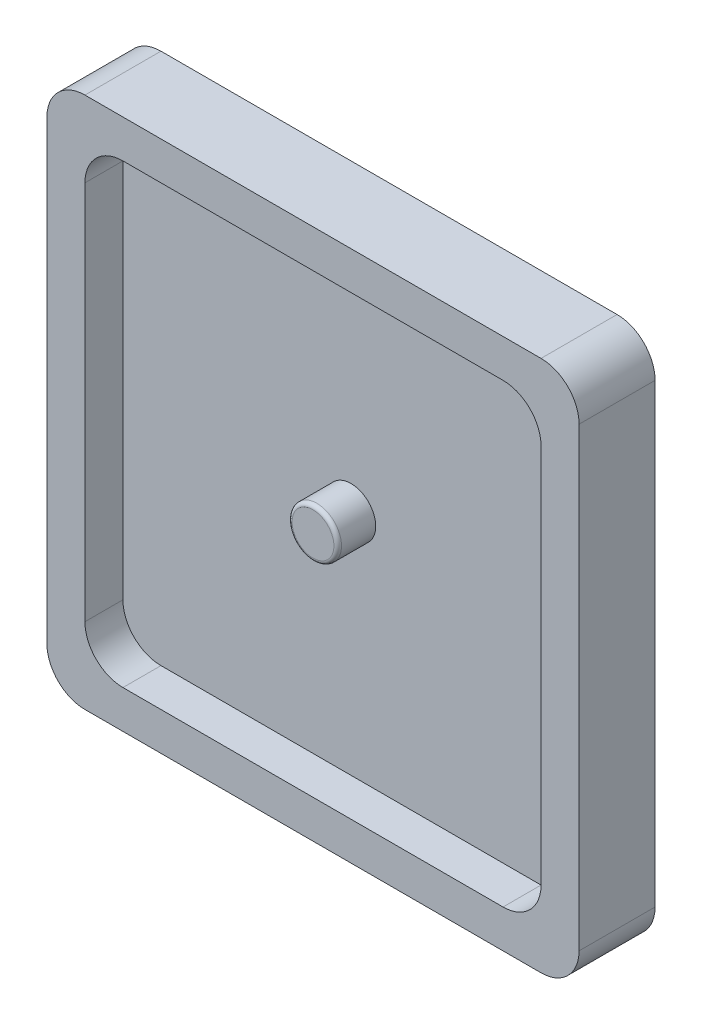
SolidWorks part; units mm, degrees
ref_plane "Plan de face" through (0, 0, 0) normal (0, 0, 1) x (1, 0, 0)
ref_plane "Plan de dessus" through (0, 0, 0) normal (0, 1, 0) x (1, 0, 0)
ref_plane "Plan de droite" through (0, 0, 0) normal (1, 0, 0) x (0, 0, -1)
sketch "Esquisse1" plane through (0, 0, 0) normal (0, 0, 1) x (1, 0, 0)
  line L1 (-70, -70) -> (70, -70)
  line L2 (-70, -70) -> (-70, 70)
  line L3 (-70, 70) -> (70, 70)
  line L4 (70, -70) -> (70, 70)
  line L5 (-70, -70) -> (70, 70) construction
  line L6 (-70, 70) -> (70, -70) construction
  point P0 (0, 0)
  dimension "D1" = 140
  dimension "D2" = 140
extrude "Boss.-Extru.1" add sketch "Esquisse1" along normal blind 20
sketch "Esquisse2" plane through (0, 0, 20) normal (0, 0, 1) x (1, 0, 0)
  line L1 (-60, -60) -> (60, -60)
  line L2 (-60, -60) -> (-60, 60)
  line L3 (-60, 60) -> (60, 60)
  line L4 (60, -60) -> (60, 60)
  line L5 (-60, -60) -> (60, 60) construction
  line L6 (-60, 60) -> (60, -60) construction
  point P0 (0, 0)
  dimension "D1" = 120
  dimension "D2" = 120
extrude "Enlèv. mat.-Extru.1" cut sketch "Esquisse2" against normal blind 10
fillet "Congé1" radius 10 4 edges at (-60, -60, 15) (60, -60, 15) (60, 60, 15) (-60, 60, 15)
fillet "Congé2" radius 10 4 edges at (70, -70, 10) (-70, -70, 10) (70, 70, 10) (-70, 70, 10)
sketch "Esquisse3" plane through (0, 0, 10) normal (0, 0, 1) x (1, 0, 0)
  circle A0 centre (0, 0) radius 6.5
  dimension "D1" = 13
extrude "Boss.-Extru.2" add sketch "Esquisse3" along normal blind 10
fillet "Congé3" radius 1 1 edges at (6.5, 0, 20)
